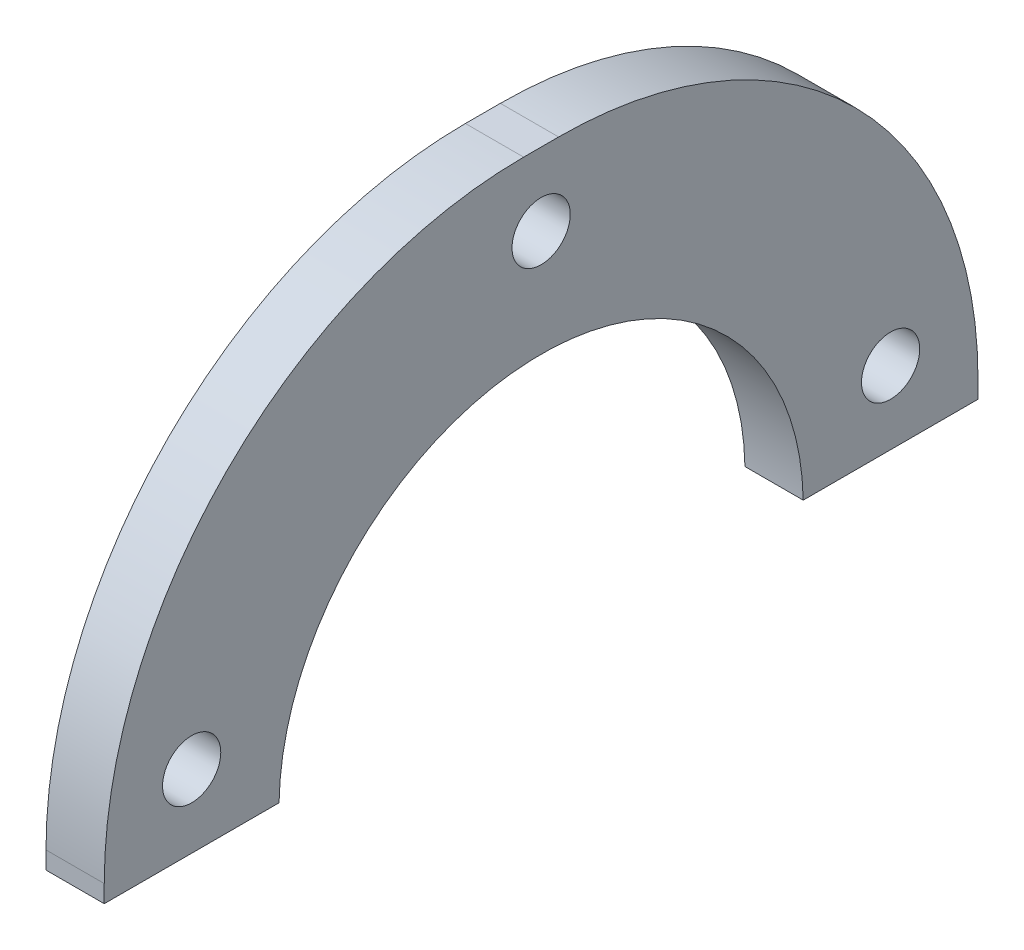
SolidWorks part; units mm, degrees
material "6061 Alloy"
ref_plane "Front Plane" through (0, 0, 0) normal (0, 0, 1) x (1, 0, 0)
ref_plane "Top Plane" through (0, 0, 0) normal (0, 1, 0) x (1, 0, 0)
ref_plane "Right Plane" through (0, 0, 0) normal (1, 0, 0) x (0, 0, -1)
sketch "Sketch1" plane through (0, 0, 0) normal (1, 0, 0) x (0, 0, -1)
  line L4 (0, 12.7) -> (0, 4.6747) construction
  line L5 (-23.8125, -11.9063) -> (23.8125, -11.9062)
  line L6 (-23.8125, -11.9063) -> (-23.8125, 11.9062)
  line L7 (23.8125, 11.9063) -> (-23.8125, 11.9062)
  line L8 (23.8125, -11.9062) -> (23.8125, 11.9063)
  line L9 (-23.8125, -11.9063) -> (23.8125, 11.9063) construction
  line L10 (-23.8125, 11.9062) -> (23.8125, -11.9062) construction
  circle A2 centre (0, -12.1603) radius 15.5575 construction
  circle A3 centre (0, 7.7851) radius 3.3274 construction
  circle A4 centre (19.6914, -7.7851) radius 3.3274 construction
  circle A5 centre (-19.6913, -7.7851) radius 3.3274 construction
  point P0 (0, 0)
  dimension "D6" = 31.115
  dimension "D7" = 6.6548
  dimension "D8" = 0.7937
  dimension "D10" = 0.7937
  dimension "D11" = 0.7937
  dimension "D12" = 1.2866
  dimension "D13" = 1.0604
  dimension "D9" = 0.7937
  dimension "D1" = 23.8125
  dimension "D2" = 0.254
  dimension "D5" = 47.625
extrude "Boss-Extrude1" add sketch "Sketch1" along normal blind 3.175
sketch "Sketch2" plane through (3.175, 0, 0) normal (1, 0, 0) x (0, 0, -1)
  line L1 (-23.8125, -11.9063) -> (23.8125, -11.9063) construction
  circle A0 centre (0, -12.1603) radius 14.2875
  dimension "D1" = 28.575
  dimension "D2" = 0.254
extrude "Cut-Extrude1" cut sketch "Sketch2" against normal through all
hole_wizard "1/8 (0.125) Diameter Hole1" positions "Sketch3" profile "Sketch4" hole size "1/8" standard "ANSI Inch"
sketch "Sketch3" plane through (3.175, 0, 0) normal (1, 0, 0) x (0, 0, -1)
  line L0 (-23.8125, -11.9063) -> (-14.2852, -11.9063) construction
  line L1 (23.8125, 11.9063) -> (-23.8125, 11.9062) construction
  line L2 (14.2852, -11.9062) -> (23.8125, -11.9062) construction
  circle A0 centre (0, 7.9375) radius 3.175 construction
  circle A1 centre (-19.0489, -7.9375) radius 3.175 construction
  circle A2 centre (19.0489, -7.9375) radius 3.175 construction
  point P0 (-19.0489, -7.9375)
  point P2 (0, 7.9375)
  point P4 (19.0489, -7.9375)
  point P12 (0, 11.9062)
  point P13 (-19.0489, -11.9063)
  point P16 (19.0489, -11.9063)
  dimension "D3" = 6.35
  dimension "D2" = 0.7937
  dimension "D1" = 0.7937
sketch "Sketch4" plane through (3.175, -7.9375, 19.0489) normal (0, 1, 0) x (0, 0, -1)
  line L0 (0, 0) -> (0, 19.9559)
  line L1 (0, 19.9559) -> (1.5875, 19.002)
  line L2 (1.5875, 19.002) -> (1.5875, 0)
  line L5 (1.5875, 0) -> (0, 0)
  line L10 (0, 19.9559) -> (-1.5875, 19.002) construction
  line L11 (0, -6.35) -> (0, 107.95) construction
  dimension "Hole Dia." = 3.175
  dimension "Hole Depth" = 19.002
  dimension "Drill Angle" = 118
fillet "Fillet1" radius 22.86 2 edges at (1.5875, 11.9063, -23.8125) (1.5875, 11.9062, 23.8125)
